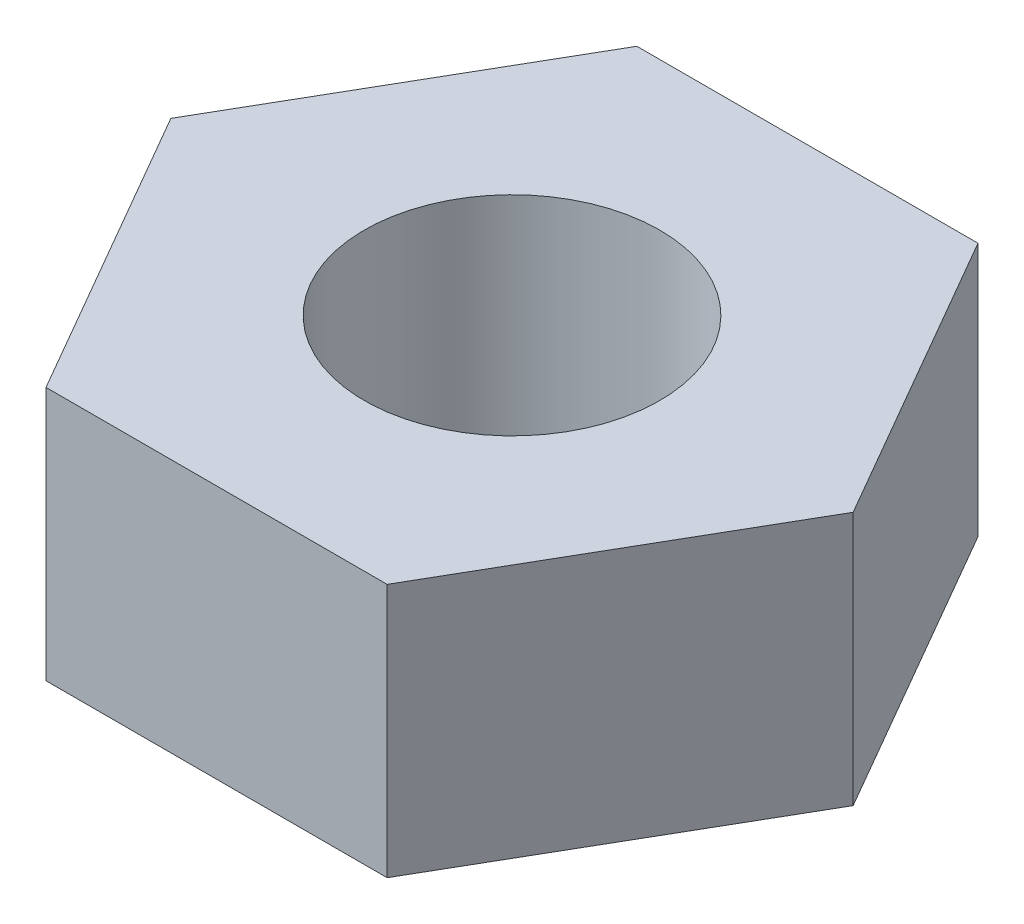
SolidWorks part; units mm, degrees
material "Nylon 101"
ref_plane "Plan de face" through (0, 0, 0) normal (0, 0, 1) x (1, 0, 0)
ref_plane "Plan de dessus" through (0, 0, 0) normal (0, 1, 0) x (1, 0, 0)
ref_plane "Plan de droite" through (0, 0, 0) normal (1, 0, 0) x (0, 0, -1)
sketch "Esquisse1" plane through (0, 0, 0) normal (0, 1, 0) x (1, 0, 0)
  line L1 (1.4434, 2.5) -> (-1.4434, 2.5)
  line L2 (-1.4434, 2.5) -> (-2.8868, 0)
  line L3 (-2.8868, 0) -> (-1.4434, -2.5)
  line L4 (-1.4434, -2.5) -> (1.4434, -2.5)
  line L5 (1.4434, -2.5) -> (2.8868, 0)
  line L6 (2.8868, 0) -> (1.4434, 2.5)
  circle A0 centre (0, 0) radius 2.5 construction
  circle A1 centre (0, 0) radius 1.25
  dimension "D2" = 2.5
  dimension "D1" = 5
extrude "Boss.-Extru.1" add sketch "Esquisse1" along normal blind 2.15
